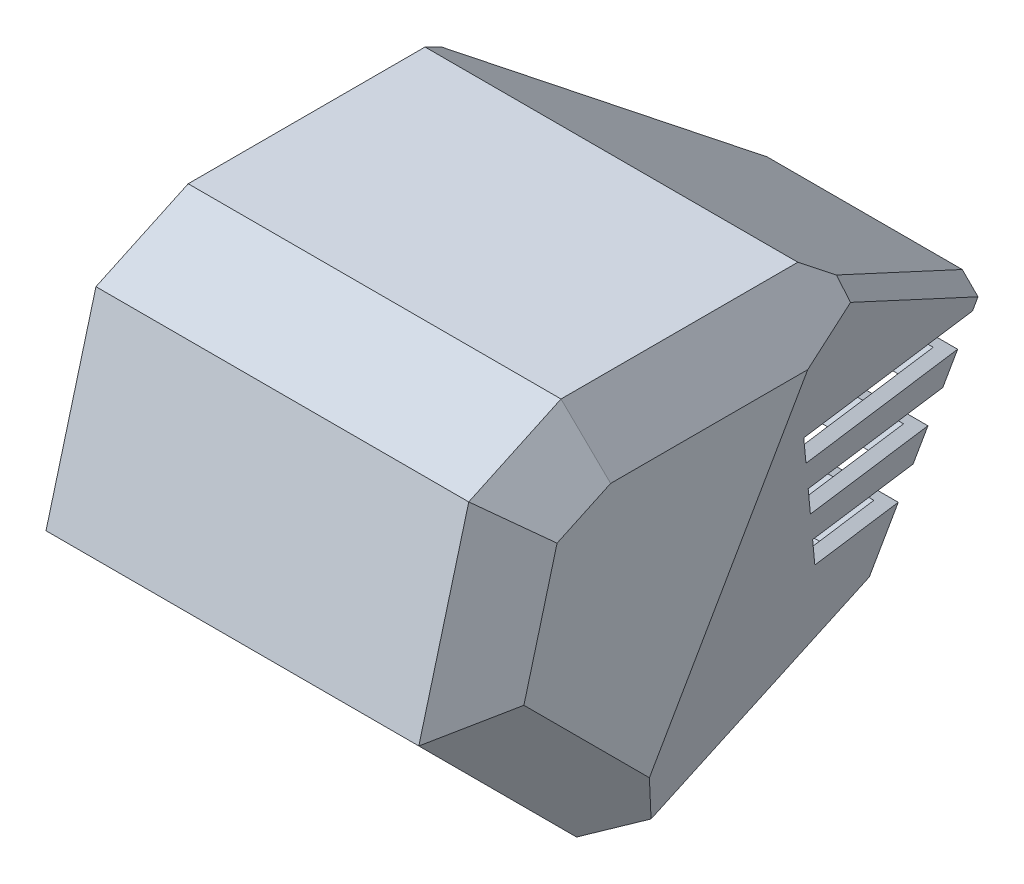
SolidWorks part; units mm, degrees
ref_plane "Plan de face" through (0, 0, 0) normal (0, 0, 1) x (1, 0, 0)
ref_plane "Plan de dessus" through (0, 0, 0) normal (0, 1, 0) x (1, 0, 0)
ref_plane "Plan de droite" through (0, 0, 0) normal (1, 0, 0) x (0, 0, -1)
sketch "Esquisse1" plane through (0, 0, 0) normal (1, 0, 0) x (0, 0, -1)
  line L0 (500, 100) -> (0, 100) construction
  line L1 (0, 0) -> (500, 0) construction
  line L2 (0, 0) -> (0, 370) construction
  line L3 (0, 370) -> (500, 370) construction
  line L4 (500, 0) -> (500, 370) construction
  line L5 (369.171, 100) -> (500, 46.1342) construction
  line L6 (500, 46.1342) -> (412.1408, 0) construction
  line L7 (412.1408, 0) -> (0, 46.1342) construction
  line L8 (0, 46.1342) -> (0, 100) construction
  line L9 (0, 100) -> (369.171, 100) construction
  line L10 (369.171, 100) -> (367.3576, 96.8592) construction
  line L11 (367.3576, 96.8592) -> (399.8941, 55.1209) construction
  line L12 (399.8941, 55.1209) -> (86.0126, 100) construction
  line L13 (369.171, 100) -> (450, 240)
  line L14 (450, 240) -> (264.3408, 370)
  line L15 (264.3408, 370) -> (99.1686, 370)
  line L16 (99.1686, 370) -> (34.8334, 340)
  line L17 (34.8334, 340) -> (0, 210)
  line L18 (0, 210) -> (110, 100)
  line L19 (450, 240) -> (500, 326.6025) construction
  line L20 (450, 240) -> (500, 240) construction
  line L21 (450, 240) -> (264.3408, 240) construction
  line L22 (264.3408, 240) -> (264.3408, 370) construction
  line L23 (99.1686, 370) -> (99.1686, 340) construction
  line L24 (34.8334, 340) -> (99.1686, 340) construction
  line L25 (0, 210) -> (34.8334, 210) construction
  line L26 (34.8334, 340) -> (34.8334, 210) construction
  line L27 (110, 100) -> (369.171, 100)
  line L28 (450, 240) -> (450, 370) construction
  line L29 (110, 100) -> (110, 210) construction
  line L30 (110, 210) -> (34.8334, 210) construction
  dimension "D1" = 500
  dimension "D2" = 370
  dimension "D3" = 100
  dimension "D4" = 60
  dimension "D5" = 140
  dimension "D6" = 35
  dimension "D7" = 50
  dimension "D8" = 15
  dimension "D9" = 25
  dimension "D10" = 45
  dimension "D11" = 110
  dimension "D12" = 240
extrude "Boss.-Extru.1" add sketch "Esquisse1" along normal blind 310
chamfer "Chanfrein1" distance 80 angle 70 2 edges at (310, 170, -409.5855) (0, 170, -409.5855)
chamfer "Chanfrein2" distance 25 angle 60 8 edges at (0, 155, -55) (0, 275, -17.4167) (0, 355, -67.001) (0, 370, -181.7547) (310, 155, -55) (310, 275, -17.4167) (310, 355, -67.001) (310, 370, -181.7547)
chamfer "Chanfrein3" distance 10 angle 45 3 edges at (155, 240, -450) (263.987, 293.7642, -373.2167) (46.013, 293.7642, -373.2167)
shell "Coque1" thickness 10
sketch "Esquisse2" plane through (0, 0, 0) normal (1, 0, 0) x (0, 0, -1)
  line L0 (441.142, 224.6575) -> (256.142, 274.2281)
  line L1 (444.9831, 231.3105) -> (369.171, 100) construction
  line L2 (256.142, 274.2281) -> (297.895, 159.5129) construction
  line L3 (297.895, 159.5129) -> (389.3782, 135)
  line L4 (389.3782, 135) -> (441.142, 224.6575) construction
  line L5 (297.895, 159.5129) -> (323.7769, 256.1054) construction
  line L6 (256.142, 274.2281) -> (264.4926, 251.2851)
  line L7 (264.4926, 251.2851) -> (430.7893, 206.726)
  line L8 (430.7893, 206.726) -> (441.142, 224.6575)
  line L9 (297.895, 159.5129) -> (289.5444, 182.4559)
  line L10 (289.5444, 182.4559) -> (399.731, 152.9315)
  line L11 (399.731, 152.9315) -> (389.3782, 135)
  line L12 (272.8432, 228.342) -> (281.1938, 205.399)
  line L13 (281.1938, 205.399) -> (410.0837, 170.863)
  line L14 (410.0837, 170.863) -> (420.4365, 188.7945)
  line L15 (420.4365, 188.7945) -> (272.8432, 228.342)
  line L16 (389.3782, 135) -> (297.895, 135) construction
  line L17 (297.895, 159.5129) -> (297.895, 135) construction
  line L18 (369.171, 100) -> (146.896, 100) construction
  line L19 (256.142, 274.2281) -> (256.142, 100) construction
  dimension "D1" = 20
  dimension "D2" = 20
  dimension "D3" = 20
  dimension "D4" = 20
  dimension "D5" = 20
  dimension "D6" = 35
  dimension "D7" = 15
  dimension "D8" = 35
  dimension "D9" = 185
extrude "Enlèv. mat.-Extru.1" cut sketch "Esquisse2" along normal through all contours L7 L8 L0 L6
